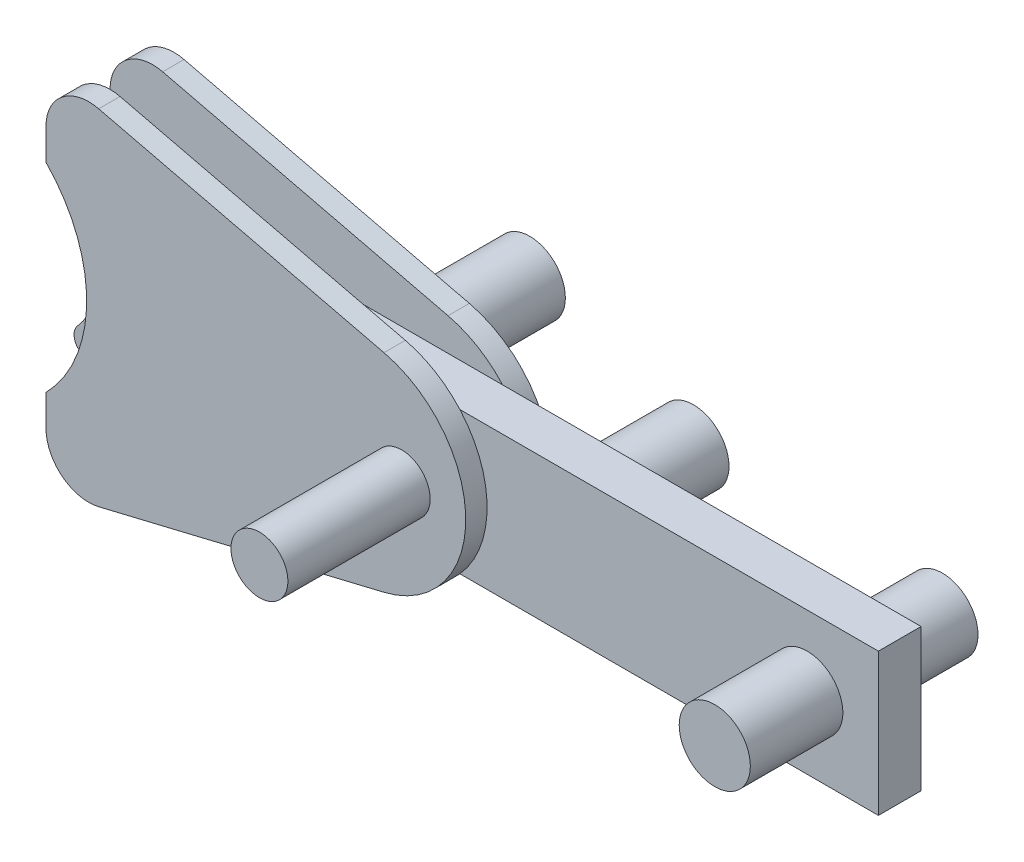
SolidWorks part; units mm, degrees
ref_plane "Front Plane" through (0, 0, 0) normal (0, 0, 1) x (1, 0, 0)
ref_plane "Top Plane" through (0, 0, 0) normal (0, 1, 0) x (1, 0, 0)
ref_plane "Right Plane" through (0, 0, 0) normal (1, 0, 0) x (0, 0, -1)
sketch "Sketch1" plane through (0, 0, 0) normal (0, 0, 1) x (1, 0, 0)
  line L1 (-35, 5) -> (25, 5)
  line L3 (-35, -5) -> (25, -5)
  line L4 (25, 5) -> (25, -5)
  arc A0 (-35, 5) -> (-35, -5) centre (-35, 0) cw
  point P0 (0, 0)
  dimension "D4" = 35
  dimension "D1" = 10
  dimension "D2" = 35
  dimension "D3" = 25
extrude "Boss-Extrude2" add sketch "Sketch1" along normal blind 1.5
sketch "Sketch2" plane through (0, 0, 1.5) normal (0, 0, 1) x (1, 0, 0)
  line L0 (-32, -9.1937) -> (-32, -7)
  line L1 (-28.2991, 12.1107) -> (-8.2477, 7.2924)
  line L2 (-28.2991, -12.1107) -> (-8.2477, -7.2924)
  line L3 (-35, -5) -> (25, -5) construction
  line L4 (-32, 7) -> (-32, 9.1937)
  arc A0 (-8.2477, -7.2924) -> (-8.2477, 7.2924) centre (-10, 0) ccw
  circle A1 centre (20, 0) radius 2.5
  arc A2 (-28.2991, 12.1107) -> (-32, 9.1937) centre (-29, 9.1937) ccw
  arc A3 (-32, -9.1937) -> (-28.2991, -12.1107) centre (-29, -9.1937) ccw
  arc A4 (-32, 7) -> (-32, -7) centre (-39.1414, 0) cw
  point P13 (-32, 13)
  point P16 (-32, -13)
  dimension "D7" = 5
  dimension "D8" = 15
  dimension "D9" = 3
  dimension "D10" = 3
  dimension "D14" = 10
  dimension "D1" = 10
  dimension "D2" = 0
  dimension "D3" = 0
  dimension "D4" = 20
  dimension "D5" = 26
  dimension "D6" = 8
  dimension "D11" = 32
  dimension "D12" = 7
  dimension "D13" = 7
extrude "Boss-Extrude3" add sketch "Sketch2" along normal blind 1.5
mirror "Mirror1" about plane through (-35, 0, 0) normal (0, 0, -1) of "Boss-Extrude2", "Boss-Extrude3"
fillet "Fillet2" radius 1 2 edges at (-35, -5, 0) (-35, 5, 0)
sketch "Sketch3" plane through (0, 0, 3) normal (0, 0, 1) x (1, 0, 0)
  line L0 (25, 5) -> (-4.4098, 5) construction
  circle A0 centre (-7, 0) radius 2
  dimension "D1" = 7
  dimension "D2" = 4
  dimension "D3" = 5
extrude "Boss-Extrude4" add sketch "Sketch3" along normal blind 10
sketch "Sketch6" plane through (0, 0, 3) normal (0, 0, 1) x (1, 0, 0)
  circle A0 centre (20, 0) radius 2.5
  dimension "D1" = 5
extrude "Boss-Extrude5" add sketch "Sketch6" along normal blind 5 and the other way blind 11
sketch "Sketch7" plane through (0, 0, -3) normal (0, 0, -1) x (-1, 0, 0)
  circle A0 centre (15, 0) radius 2.5
  circle A1 centre (-20, 0) radius 2.5 construction
  dimension "D1" = 5
  dimension "D2" = 35
extrude "Boss-Extrude6" add sketch "Sketch7" along normal blind 11
sketch "Sketch8" plane through (0, 0, -1.5) normal (0, 0, -1) x (-1, 0, 0)
  circle A0 centre (-1, 0) radius 2.5
  dimension "D1" = 1
extrude "Boss-Extrude7" add sketch "Sketch8" along normal blind 8
